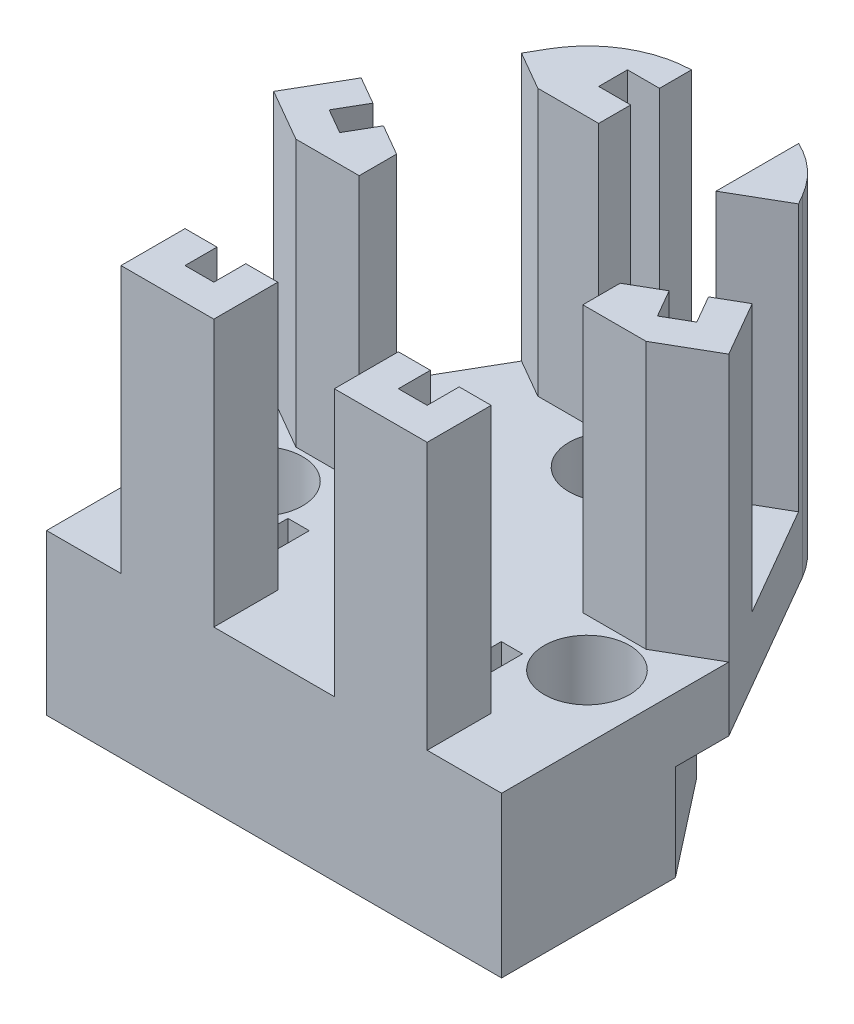
SolidWorks part; units mm, degrees
material "CA"
ref_plane "Front Plane" through (0, 0, 0) normal (0, 0, 1) x (1, 0, 0)
ref_plane "Top Plane" through (0, 0, 0) normal (0, 1, 0) x (1, 0, 0)
ref_plane "Right Plane" through (0, 0, 0) normal (1, 0, 0) x (0, 0, -1)
sketch "Sketch1" plane through (0, 0, 0) normal (0, 1, 0) x (1, 0, 0)
  line L0 (-6.5, 0) -> (6.5, 0) construction
  line L1 (-6.5, 0) -> (-16.0607, -16.5595) construction
  line L2 (0, 0) -> (0, -22.1581) construction
  line L3 (-21.3279, -16.9826) -> (-16.4146, -19.8193)
  line L5 (6.5, 0) -> (16.0607, -16.5595) construction
  line L7 (-3.5, 4.35) -> (-9.0115, 4.35)
  line L12 (-6.5, 1.35) -> (-6.5, -1.35)
  line L14 (-16.0607, -16.5595) -> (-17.2298, -15.8845)
  line L17 (-18.3279, -11.7865) -> (-21.3279, -16.9826)
  line L22 (-14.8915, -17.2345) -> (-16.0607, -16.5595)
  line L25 (-10, -35.2789) -> (-11.35, -35.2789)
  line L27 (-11.35, -32.2789) -> (-14.35, -32.2789)
  line L29 (-14.35, -38.2789) -> (-5.65, -38.2789)
  line L33 (-8.65, -35.2789) -> (-10, -35.2789)
  line L36 (-12.8279, -2.2602) -> (-9.2082, -4.35)
  line L80 (7.5, 4.35) -> (7.5, -4.35)
  line L95 (-3.5, 4.35) -> (-3.5, 1.35)
  line L96 (-3.5, 1.35) -> (-6.5, 1.35)
  line L97 (-3.5, -4.35) -> (-3.5, -1.35)
  line L98 (-3.5, -1.35) -> (-6.5, -1.35)
  line L99 (-18.3279, -11.7865) -> (-15.7298, -13.2865)
  line L100 (-15.7298, -13.2865) -> (-17.2298, -15.8845)
  line L101 (-10.4819, -16.3163) -> (-13.3915, -14.6365)
  line L102 (-13.3915, -14.6365) -> (-14.8915, -17.2345)
  line L104 (-11.35, -32.2789) -> (-11.35, -35.2789)
  line L105 (-5.65, -32.2789) -> (-8.65, -32.2789)
  line L106 (-8.65, -32.2789) -> (-8.65, -35.2789)
  line L131 (-3.5, -4.35) -> (0, -4.35)
  line L134 (-10.4819, -16.3163) -> (-10.4819, -19.8193)
  line L135 (-16.4146, -19.8193) -> (-10.4819, -19.8193)
  line L136 (18.3279, -11.7865) -> (21.3279, -16.9826)
  line L137 (18.3279, -11.7865) -> (15.7298, -13.2865)
  line L138 (15.7298, -13.2865) -> (17.2298, -15.8845)
  line L139 (16.0607, -16.5595) -> (17.2298, -15.8845)
  line L140 (14.8915, -17.2345) -> (16.0607, -16.5595)
  line L141 (13.3915, -14.6365) -> (14.8915, -17.2345)
  line L142 (10.4819, -16.3163) -> (13.3915, -14.6365)
  line L143 (10.4819, -16.3163) -> (10.4819, -19.8193)
  line L144 (16.4146, -19.8193) -> (10.4819, -19.8193)
  line L145 (21.3279, -16.9826) -> (16.4146, -19.8193)
  line L146 (7.5, 4.35) -> (9.0115, 4.35)
  line L147 (-14.35, -32.2789) -> (-14.35, -38.2789)
  line L148 (-5.65, -32.2789) -> (-5.65, -38.2789)
  line L149 (5.65, -32.2789) -> (5.65, -38.2789)
  line L150 (14.35, -32.2789) -> (14.35, -38.2789)
  line L151 (8.65, -32.2789) -> (8.65, -35.2789)
  line L152 (5.65, -32.2789) -> (8.65, -32.2789)
  line L153 (11.35, -32.2789) -> (11.35, -35.2789)
  line L154 (8.65, -35.2789) -> (10, -35.2789)
  line L155 (14.35, -38.2789) -> (5.65, -38.2789)
  line L156 (11.35, -32.2789) -> (14.35, -32.2789)
  line L157 (10, -35.2789) -> (11.35, -35.2789)
  line L158 (-12.8279, -2.2602) -> (-9.0115, 4.35)
  line L159 (-3.5, -4.35) -> (-9.2082, -4.35)
  line L163 (12.4008, -1.5205) -> (9.0115, 4.35)
  line L164 (7.5, -4.35) -> (12.4008, -1.5205)
  point P2 (0, 0)
  dimension "D1" = 13
  dimension "D3" = 120
  dimension "D4" = 3
  dimension "D5" = 1.35
  dimension "D6" = 1.35
  dimension "D7" = 3
  dimension "D8" = 1.35
  dimension "D9" = 1.35
  dimension "D10" = 1.35
  dimension "D11" = 3
  dimension "D12" = 1.35
  dimension "D13" = 3
  dimension "D14" = 3
  dimension "D15" = 3
  dimension "D16" = 3
  dimension "D17" = 3
  dimension "D18" = 3
  dimension "D20" = 3
  dimension "D26" = 14
  dimension "D27" = 14
  dimension "D29" = 10
  dimension "D30" = 3
extrude "Boss-Extrude1" add sketch "Sketch1" along normal blind 25
sketch "Sketch2" plane through (0, 0, 0) normal (0, -1, 0) x (-1, 0, 0)
  line L19 (-21.3279, -16.9826) -> (-9.0115, 4.35)
  line L20 (-9.0115, 4.35) -> (9.0115, 4.35)
  line L21 (9.0115, 4.35) -> (21.3279, -16.9826)
  line L22 (21.3279, -16.9826) -> (21.3279, -38.2789)
  line L23 (-21.3279, -16.9826) -> (-21.3279, -38.2789)
  line L24 (21.3279, -38.2789) -> (-21.3279, -38.2789)
extrude "Boss-Extrude2" add sketch "Sketch2" along normal blind 15
sketch "Sketch3" plane through (0, 0, 0) normal (0, 1, 0) x (1, 0, 0)
  line L0 (0, 4.35) -> (0, -38.2789) construction
  line L2 (5.65, -38.2789) -> (-5.65, -38.2789) construction
  line L5 (-16.0607, -16.5595) -> (-9.4402, -5.0925) construction
  line L7 (-10, -35.2789) -> (-10, -22.0821) construction
  line L10 (-2.6, -1) -> (2.8, -1)
  line L11 (-2.6, -1) -> (-2.6, 1)
  line L12 (-2.6, 1) -> (2.8, 1)
  line L13 (2.8, -1) -> (2.8, 1)
  line L14 (-2.6, -1) -> (2.8, 1) construction
  line L15 (-2.6, 1) -> (2.8, -1) construction
  line L16 (-14.9767, -12.6821) -> (-13.2446, -13.6821)
  line L17 (-13.2446, -13.6821) -> (-10.5446, -9.0055)
  line L18 (-10.5446, -9.0055) -> (-12.2767, -8.0055)
  line L19 (-12.2767, -8.0055) -> (-14.9767, -12.6821)
  line L21 (11, -25.9789) -> (9, -25.9789)
  line L22 (-11, -31.3789) -> (-9, -31.3789)
  line L23 (-11, -31.3789) -> (-11, -25.9789)
  line L24 (-11, -25.9789) -> (-9, -25.9789)
  line L25 (-9, -31.3789) -> (-9, -25.9789)
  line L26 (-11, -31.3789) -> (-9, -25.9789) construction
  line L27 (-11, -25.9789) -> (-9, -31.3789) construction
  line L28 (9, -31.3789) -> (9, -25.9789)
  line L29 (11, -31.3789) -> (9, -31.3789)
  line L30 (11, -31.3789) -> (11, -25.9789)
  line L31 (10.5446, -9.0055) -> (12.2767, -8.0055)
  line L32 (13.2446, -13.6821) -> (10.5446, -9.0055)
  line L33 (14.9767, -12.6821) -> (13.2446, -13.6821)
  line L34 (12.2767, -8.0055) -> (14.9767, -12.6821)
  line L39 (-14.8915, -17.2345) -> (-17.2298, -15.8845) construction
  line L42 (-3.5, 4.35) -> (7.5, 4.35) construction
  line L43 (-8.65, -35.2789) -> (-11.35, -35.2789) construction
  line L44 (-21.3279, -38.2789) -> (-21.3279, -16.9826) construction
  line L45 (-14.35, -38.2789) -> (-21.3279, -38.2789) construction
  line L46 (-6.5, 1.35) -> (-6.5, -1.35) construction
  circle A0 centre (-15.3279, -24.2789) radius 1.55
  circle A1 centre (0, -6.65) radius 1.55
  circle A2 centre (15.3279, -24.2789) radius 1.55
  point P19 (0.1, 0)
  point P33 (-10, -28.6789)
  dimension "D13" = 3.1
  dimension "D14" = 3.1
  dimension "D2" = 6
  dimension "D1" = 5.4
  dimension "D3" = 2
  dimension "D4" = 2
  dimension "D5" = 5.4
  dimension "D6" = 14
  dimension "D7" = 2
  dimension "D8" = 3.9
  dimension "D9" = 5.4
  dimension "D10" = 11
  dimension "D15" = 3.9
  dimension "D16" = 1
extrude "Cut-Extrude1" cut sketch "Sketch3" against normal through all contours A1 | L21 L28 L29 L30 | A2 | L31 L34 L33 L32 | L11 L10 L13 L12 | L23 L22 L25 L24 | A0 | L19 L16 L17 L18
sketch "Sketch4" plane through (0, 0, 0) normal (0, 1, 0) x (1, 0, 0)
  line L1 (-3.5, 4.35) -> (9.0115, 4.35) construction
  circle A0 centre (-15.3279, -24.2789) radius 4
  circle A1 centre (0, -6.65) radius 4
  circle A2 centre (15.3279, -24.2789) radius 4
  dimension "D1" = 8
  dimension "D2" = 11
extrude "Cut-Extrude2" cut sketch "Sketch4" against normal blind 10
sketch "Sketch17" plane through (0, -15, 0) normal (0, -1, 0) x (-1, 0, 0)
  line L0 (0, 4.35) -> (0, -41.2168) construction
  line L1 (9.0115, 4.35) -> (-9.0115, 4.35) construction
  line L2 (7.0115, -3.65) -> (-7.0115, -3.65)
  line L3 (21.3279, -21.9826) -> (7.0115, -3.65)
  line L5 (21.3279, -38.2789) -> (21.3279, -16.9826) construction
  line L6 (21.3279, -21.9826) -> (21.3279, -16.9826)
  line L7 (21.3279, -16.9826) -> (9.0115, 4.35)
  line L9 (21.3279, -16.9826) -> (9.0115, 4.35)
  line L10 (9.0115, 4.35) -> (-9.0115, 4.35)
  line L11 (-21.3279, -16.9826) -> (-9.0115, 4.35)
  line L12 (-21.3279, -16.9826) -> (-9.0115, 4.35)
  line L13 (-21.3279, -21.9826) -> (-21.3279, -16.9826)
  line L14 (-21.3279, -21.9826) -> (-7.0115, -3.65)
  point P17 (0, -3.65)
  dimension "D1" = 8
  dimension "D2" = 2
  dimension "D3" = 5
extrude "Cut-Extrude12" cut sketch "Sketch17" against normal blind 9
sketch "Sketch18" plane through (0, -15, 0) normal (0, -1, 0) x (-1, 0, 0)
  line L0 (9.0115, 4.35) -> (-9.0115, 4.35) construction
  circle A1 centre (0, -17.65) radius 7.5
  dimension "D1" = 22
  dimension "D2" = 15
extrude "Cut-Extrude13" cut sketch "Sketch18" against normal blind 3
fillet "Fillet1" radius 10 2 edges at (-9.0115, 9.5, -4.35) (9.0115, 9.5, -4.35)
